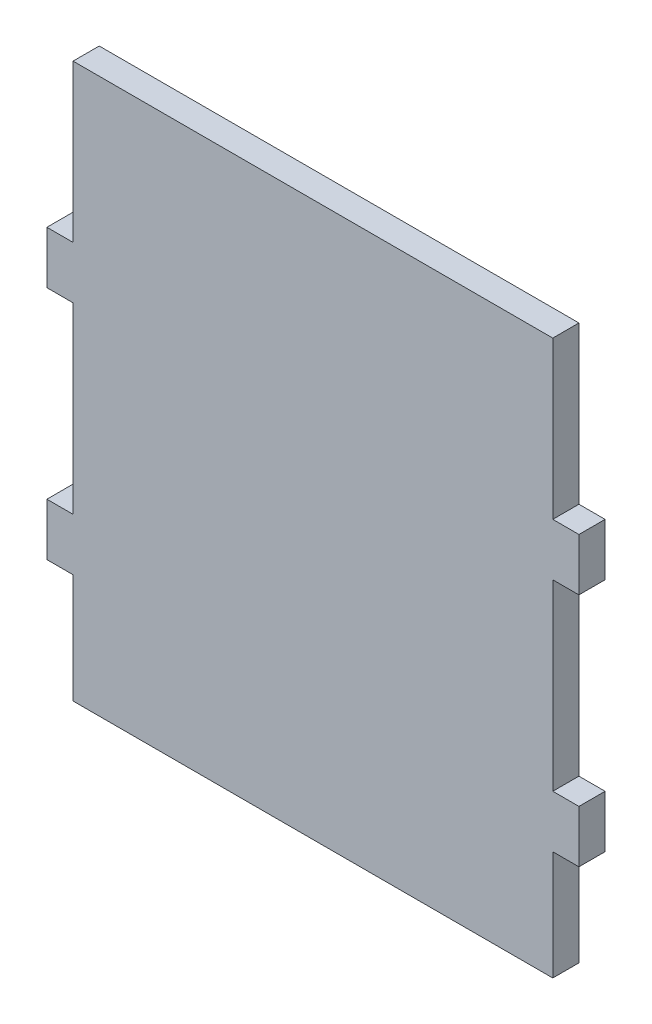
SolidWorks part; units mm, degrees
ref_plane "Přední rovina" through (0, 0, 0) normal (0, 0, 1) x (1, 0, 0)
ref_plane "Horní rovina" through (0, 0, 0) normal (0, 1, 0) x (1, 0, 0)
ref_plane "Pravá rovina" through (0, 0, 0) normal (1, 0, 0) x (0, 0, -1)
sketch "Skica1" plane through (0, 0, 0) normal (0, 0, 1) x (1, 0, 0)
  line L0 (0, 0) -> (55, 0)
  line L1 (0, 0) -> (0, -18)
  line L2 (55, 0) -> (55, -18)
  line L3 (0, -63.54) -> (55, -63.54)
  line L4 (0, -18) -> (-3, -18)
  line L5 (0, -24) -> (-3, -24)
  line L6 (-3, -18) -> (-3, -24)
  line L7 (0, -45) -> (-3, -45)
  line L8 (0, -51) -> (-3, -51)
  line L9 (-3, -45) -> (-3, -51)
  line L10 (55, -51) -> (58, -51)
  line L11 (58, -45) -> (58, -51)
  line L12 (55, -45) -> (58, -45)
  line L13 (55, -18) -> (58, -18)
  line L14 (55, -24) -> (58, -24)
  line L15 (58, -18) -> (58, -24)
  line L16 (55, -51) -> (55, -63.54)
  line L17 (55, -24) -> (55, -45)
  line L18 (0, -24) -> (0, -45)
  line L19 (0, -51) -> (0, -63.54)
  dimension "D1" = 55
  dimension "D2" = 63.54
  dimension "D3" = 3
  dimension "D4" = 3
  dimension "D5" = 6
  dimension "D6" = 6
  dimension "D7" = 18
  dimension "D8" = 21
  dimension "D9" = 6
  dimension "D10" = 6
  dimension "D11" = 18
  dimension "D12" = 21
  dimension "D13" = 3
  dimension "D14" = 3
extrude "Přidat vysunutím1" add sketch "Skica1" along normal blind 3
